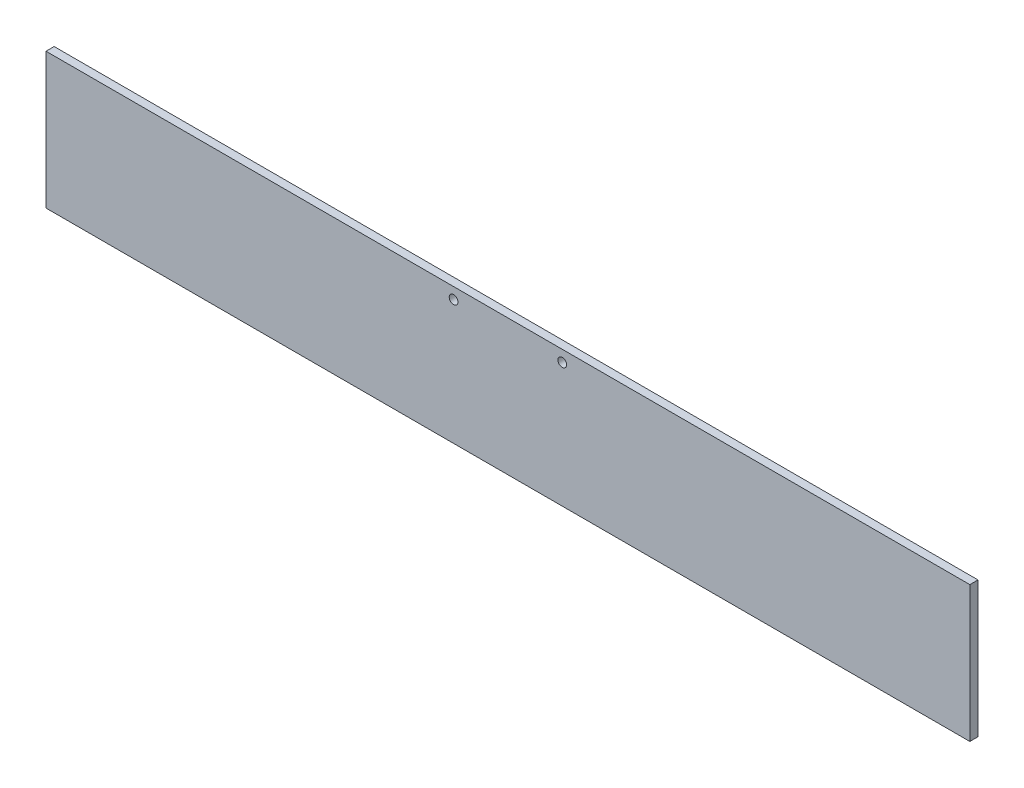
SolidWorks part; units mm, degrees
material "Perspex (TM) GS Acrylic Cast Sheet"
ref_plane "Front Plane" through (0, 0, 0) normal (0, 0, 1) x (1, 0, 0)
ref_plane "Top Plane" through (0, 0, 0) normal (0, 1, 0) x (1, 0, 0)
ref_plane "Right Plane" through (0, 0, 0) normal (1, 0, 0) x (0, 0, -1)
sketch "Sketch1" plane through (0, 0, 0) normal (0, 0, 1) x (1, 0, 0)
  line L1 (0, 0) -> (340, 0)
  line L2 (0, 0) -> (0, 50)
  line L3 (0, 50) -> (340, 50)
  line L4 (340, 0) -> (340, 50)
  dimension "D1" = 340
  dimension "D2" = 50
extrude "Boss-Extrude1" add sketch "Sketch1" along normal blind 3
sketch "Sketch2" plane through (0, 0, 3) normal (0, 0, 1) x (1, 0, 0)
  circle A0 centre (150, 45.827) radius 1.6 construction
  circle A1 centre (190, 45.827) radius 1.6 construction
  circle A2 centre (150, 45.827) radius 1.6
  circle A3 centre (190, 45.827) radius 1.6
extrude "Cut-Extrude1" cut sketch "Sketch2" against normal up to next
